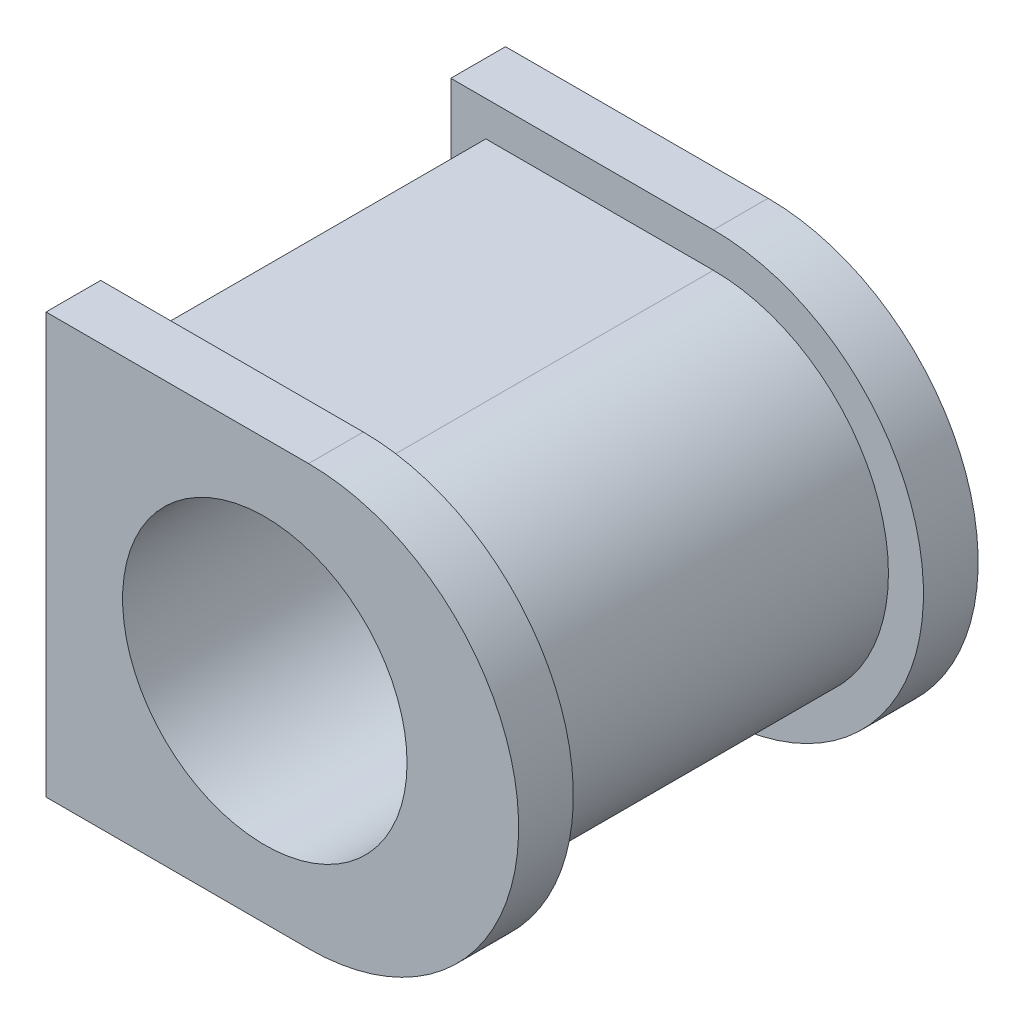
SolidWorks part; units mm, degrees
ref_plane "Front Plane" through (0, 0, 0) normal (0, 0, 1) x (1, 0, 0)
ref_plane "Top Plane" through (0, 0, 0) normal (0, 1, 0) x (1, 0, 0)
ref_plane "Right Plane" through (0, 0, 0) normal (1, 0, 0) x (0, 0, -1)
sketch "Sketch1" plane through (0, 0, 0) normal (0, 0, 1) x (1, 0, 0)
  line L1 (-26, -40) -> (26, -40)
  line L2 (-26, -40) -> (-26, 40)
  line L3 (-26, 40) -> (26, 40)
  line L5 (-26, -40) -> (26, 40) construction
  line L6 (-26, 40) -> (26, -40) construction
  arc A1 (26, -40) -> (26, 40) centre (26, 0) ccw
  circle A2 centre (16, 0) radius 32.5
  point P0 (0, 0)
  dimension "D3" = 65
  dimension "D1" = 80
  dimension "D2" = 52
  dimension "D4" = 10
extrude "Boss-Extrude1" add sketch "Sketch1" along normal mid plane 80
sketch "Sketch2" plane through (0, 0, 40) normal (0, 0, 1) x (1, 0, 0)
  line L15 (26, 48) -> (-34, 48)
  line L16 (-34, -48) -> (26, -48)
  line L17 (-34, 48) -> (-34, -48)
  line L18 (26, 48) -> (-34, 48)
  line L19 (-34, -48) -> (26, -48)
  line L20 (-34, 48) -> (-34, -48)
  circle A2 centre (16, 0) radius 32.5 construction
  arc A3 (26, -48) -> (26, 48) centre (26, 0) ccw
  arc A4 (26, -48) -> (26, 48) centre (26, 0) ccw
  circle A5 centre (16, 0) radius 32.5
  dimension "D1" = 8
  dimension "D2" = 8
extrude "Boss-Extrude4" add sketch "Sketch2" along normal blind 12.5
mirror "Mirror1" about plane through (0, 0, 0) normal (0, 0, 1) of "Boss-Extrude4"
